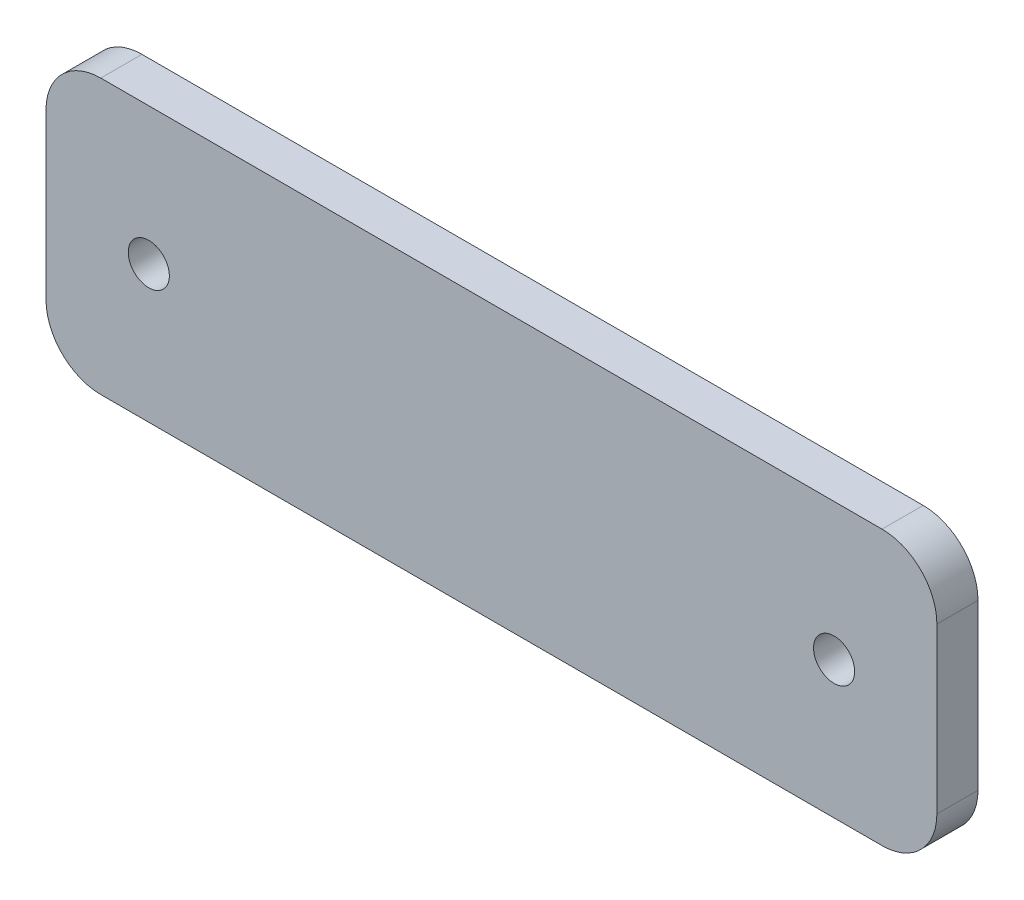
SolidWorks part; units mm, degrees
ref_plane "前视基准面" through (0, 0, 0) normal (0, 0, 1) x (1, 0, 0)
ref_plane "上视基准面" through (0, 0, 0) normal (0, 1, 0) x (1, 0, 0)
ref_plane "右视基准面" through (0, 0, 0) normal (1, 0, 0) x (0, 0, -1)
other "Configuration Table"
sketch "草图1" plane through (0, 0, 0) normal (0, 0, 1) x (1, 0, 0)
  line L1 (-32.5, 10) -> (32.5, 10)
  line L2 (-32.5, 10) -> (-32.5, -10)
  line L3 (-32.5, -10) -> (32.5, -10)
  line L4 (32.5, 10) -> (32.5, -10)
  dimension "D1" = 20
  dimension "D2" = 65
  dimension "D3" = 32.5
  dimension "D4" = 10
extrude "凸台-拉伸1" add sketch "草图1" along normal blind 3
sketch "草图2" plane through (0, 0, 3) normal (0, 0, 1) x (1, 0, 0)
  circle A0 centre (25, 0) radius 1.5
  circle A1 centre (-25, 0) radius 1.5
  point P4 (0, 0)
  point P6 (0, 0)
  point P8 (-18.868, 0.8079)
  dimension "D1" = 50
  dimension "D3" = 3
  dimension "D2" = 25
extrude "切除-拉伸1" cut sketch "草图2" against normal blind 3
fillet "圆角1" radius 4 4 edges at (-32.5, -10, 1.5) (-32.5, 10, 1.5) (32.5, -10, 1.5) (32.5, 10, 1.5)
